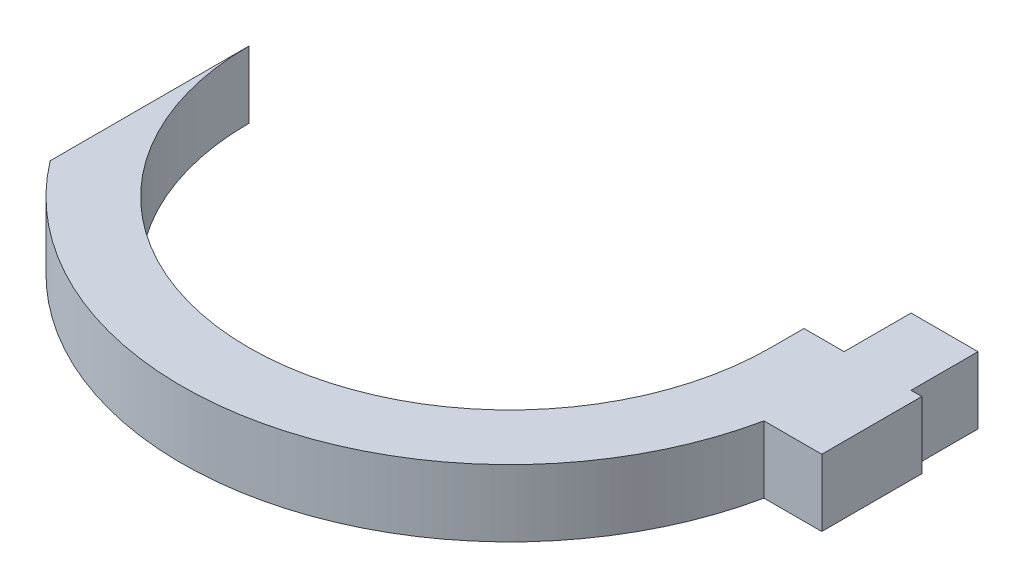
SolidWorks part; units mm, degrees
ref_plane "Front Plane" through (0, 0, 0) normal (0, 0, 1) x (1, 0, 0)
ref_plane "Top Plane" through (0, 0, 0) normal (0, 1, 0) x (1, 0, 0)
ref_plane "Right Plane" through (0, 0, 0) normal (1, 0, 0) x (0, 0, -1)
sketch "Sketch1" plane through (0, 0, 0) normal (0, 1, 0) x (1, 0, 0)
  line L0 (53.34, 3.1377) -> (53.34, 9.4877)
  line L1 (53.34, 9.4877) -> (59.69, 9.4877)
  line L2 (59.69, 9.4877) -> (59.69, 3.1377)
  line L3 (49.53, 0) -> (49.53, 3.1377)
  line L4 (0, 0) -> (0, -18.8371)
  line L5 (49.53, 3.1377) -> (53.34, 3.1377)
  line L6 (60.706, 0) -> (60.706, -6.35)
  line L7 (60.706, -6.35) -> (55.2251, -6.35)
  line L8 (60.706, 0) -> (60.706, 3.1377)
  line L9 (60.706, 3.1377) -> (59.69, 3.1377)
  arc A0 (49.53, 0) -> (0, 0) centre (24.765, 0) cw
  arc A1 (0, -18.8371) -> (55.2251, -6.35) centre (24.765, 0) ccw
  dimension "D1" = 24.765
  dimension "D5" = 6.35
  dimension "D4" = 6.35
  dimension "D2" = 3.81
  dimension "D3" = 6.35
  dimension "D6" = 3.1377
  dimension "D7" = 1.016
extrude "Boss-Extrude1" add sketch "Sketch1" along normal blind 6.35
equation "\"Ball Diameter\"= 1.75in"
equation "\"Sheet Thickness\"= 0.25in"
equation "\"Screw Diameter\"= .17in"
equation "\"Robot Diameter\"= 14in"
equation "\"Castor Screw Diameter\"= 0.22in"
equation "\"Wheel Diameter\" = 4in"
equation "\"Nut Diameter\" = 8.4mm"
equation "\"Nut Height\" = 2.9mm"
equation "\"Screw Height\" = 0.55in"
equation "\"Pulley Diameter\" = 1in"
equation "\"Reactor Height\" = 14in"
equation "\"Elevator Height\" = 11.5in"
equation "\"Elevator Width\" = \"Ball Diameter\" + 0.25in"
equation "\"Elevator Bearing Diameter\" = sqr(2*(\"Sheet Thickness\"^2)) + 0.2in"
equation "\"Elevator Axle Endcap Diameter\" = \"Pulley Diameter\" + 0.25in"
equation "\"Elevator Axle Length\" = \"Elevator Width\" + 8*\"Sheet Thickness\""
equation "\"Elevator Clearance from Axis\" = 3.28in"
equation "\"D1@Sketch1\"=\"Claw Radius\""
equation "\"D3@Sketch1\"=\"Sheet Thickness\""
equation "\"D4@Sketch1\"=\"Sheet Thickness\""
equation "\"D5@Sketch1\"=\"Sheet Thickness\""
equation "\"D1@Boss-Extrude1\"=\"Sheet Thickness\""
equation "\"D6@Sketch1\"=(\"Claw Radius\")*(1 -  sin(arccos((\"Claw Horizontal Seperation\"/\"Claw Radius\"))))"
equation "\"Claw Horizontal Seperation\" = (\"Elevator Width\"/2) - (1.5 * \"Sheet Thickness\") - 0.15in"
equation "\"Ball Radius\" = \"Ball Diameter\"/2"
equation "\"Claw Radius\" = \"Ball Radius\" + 0.1in"
